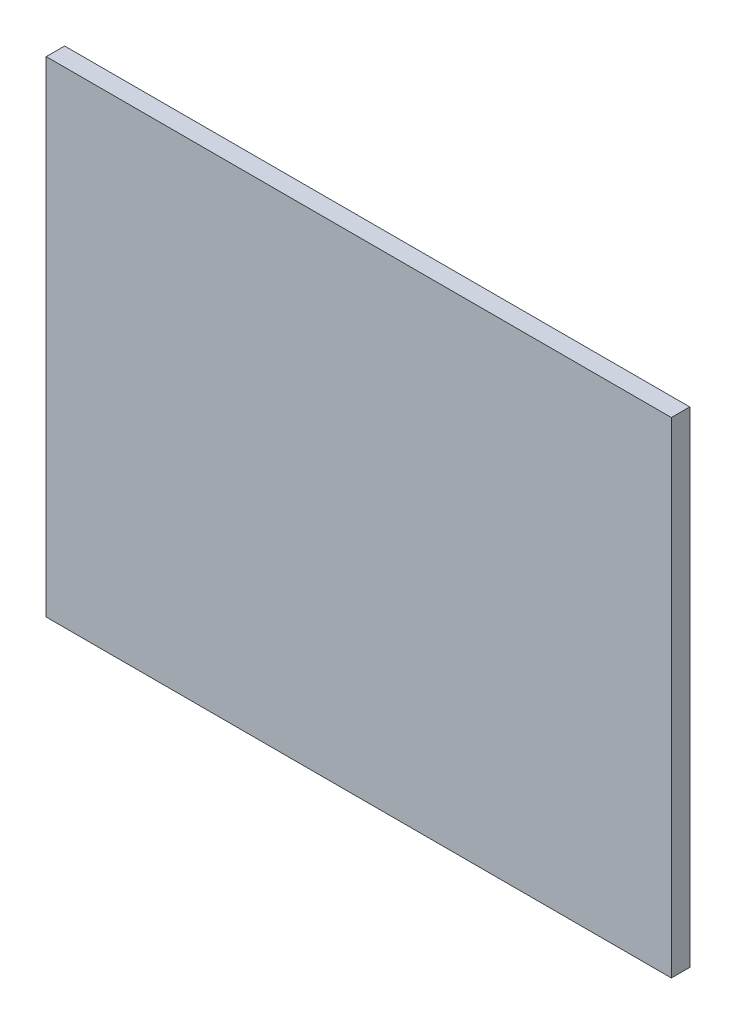
SolidWorks part; units mm, degrees
ref_plane "Front Plane" through (0, 0, 0) normal (0, 0, 1) x (1, 0, 0)
ref_plane "Top Plane" through (0, 0, 0) normal (0, 1, 0) x (1, 0, 0)
ref_plane "Right Plane" through (0, 0, 0) normal (1, 0, 0) x (0, 0, -1)
sketch "Sketch1" plane through (0, 0, 0) normal (0, 0, 1) x (1, 0, 0)
  line L1 (-39.4308, 36.3846) -> (45.5692, 36.3846)
  line L2 (-39.4308, 36.3846) -> (-39.4308, -29.6154)
  line L3 (-39.4308, -29.6154) -> (45.5692, -29.6154)
  line L4 (45.5692, 36.3846) -> (45.5692, -29.6154)
  dimension "D1" = 66
  dimension "D2" = 85
extrude "Boss-Extrude1" add sketch "Sketch1" along normal blind 2.5
